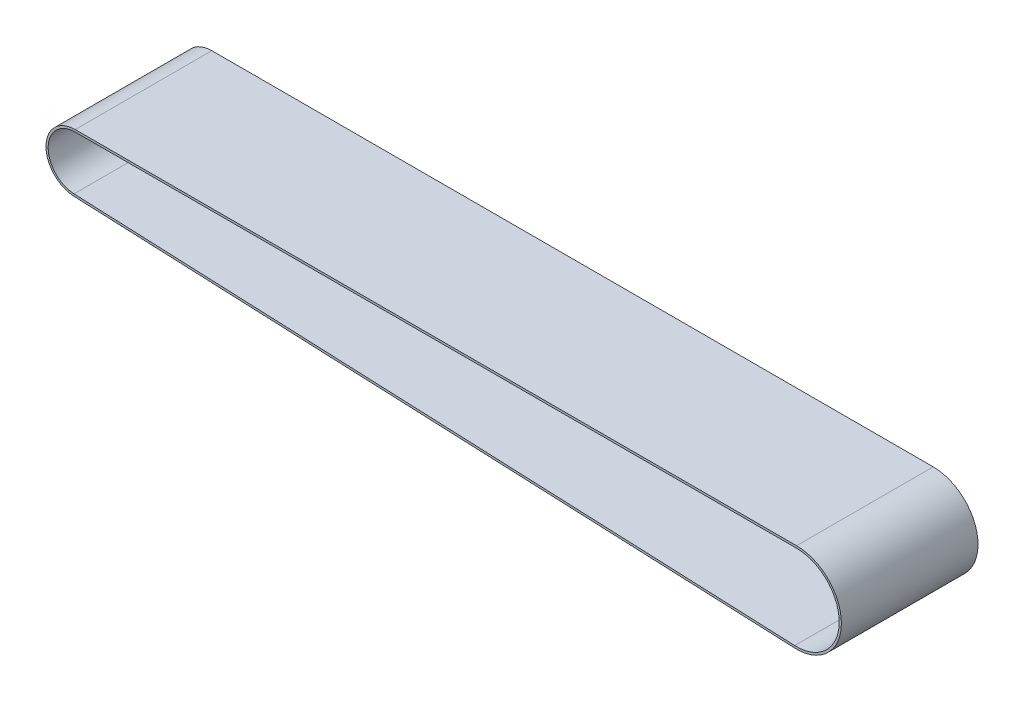
SolidWorks part; units mm, degrees
material "Märtens PU-G/2"
ref_plane "Vorne" through (0, 0, 0) normal (0, 0, 1) x (1, 0, 0)
ref_plane "Oben" through (0, 0, 0) normal (0, 1, 0) x (1, 0, 0)
ref_plane "Rechts" through (0, 0, 0) normal (1, 0, 0) x (0, 0, -1)
sketch "Skizze2" plane through (0, 0, 0) normal (0, 0, 1) x (1, 0, 0)
  line L0 (0, 0) -> (1, 0) construction
  line L1 (0, 0) -> (0, 1) construction
  line L2 (-0.0094, 24.75) -> (659.9852, 25)
  line L3 (658.3314, -52.9643) -> (-1.0589, -24.7273)
  arc A0 (-1.0589, -24.7273) -> (-0.0094, 24.75) centre (0, 0) cw
  arc A1 (659.9852, 25) -> (658.3314, -52.9643) centre (660, -14) cw
extrude "Linear-Austragen-Dünn1" add sketch "Skizze2" along normal mid plane 125 thin thin type one direction wall 2
